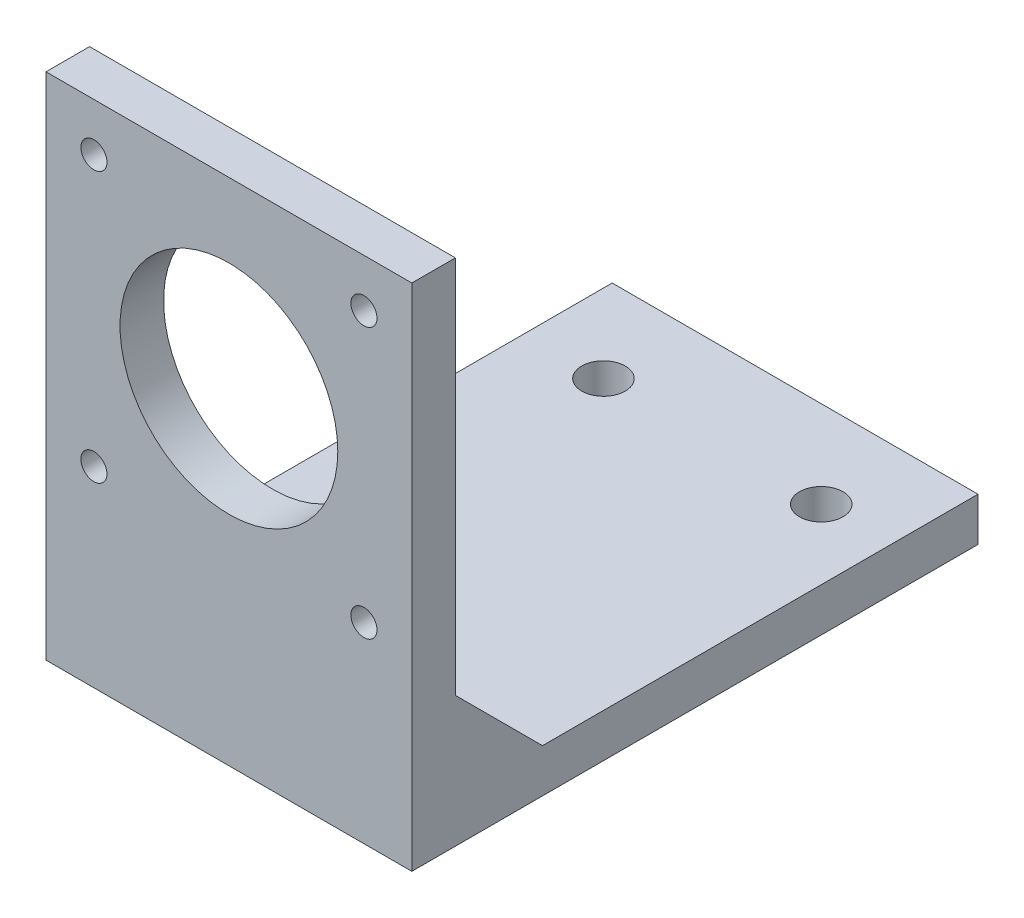
SolidWorks part; units mm, degrees
ref_plane "前视基准面" through (0, 0, 0) normal (0, 0, 1) x (1, 0, 0)
ref_plane "上视基准面" through (0, 0, 0) normal (0, 1, 0) x (1, 0, 0)
ref_plane "右视基准面" through (0, 0, 0) normal (1, 0, 0) x (0, 0, -1)
sketch "草图1" plane through (0, 0, 0) normal (0, 1, 0) x (0, 0, -1)
  line L1 (0, 0) -> (-60, 0)
  line L2 (0, 0) -> (0, 42)
  line L3 (0, 42) -> (-60, 42)
  line L4 (-60, 0) -> (-60, 42)
  circle A0 centre (-10, 33) radius 2.5
  circle A1 centre (-10, 8) radius 2.5
  dimension "D3" = 25
  dimension "D4" = 5
  dimension "D5" = 8
  dimension "D1" = 42
  dimension "D2" = 60
  dimension "D6" = 10
extrude "凸台-拉伸1" add sketch "草图1" along normal blind 5
sketch "草图2" plane through (0, 0, 60) normal (0, 0, 1) x (1, 0, 0)
  line L0 (0, 5) -> (0, 0) construction
  line L5 (-42, 0) -> (0, 0)
  line L6 (-42, 0) -> (-42, 58.5)
  line L7 (-42, 58.5) -> (0, 58.5)
  line L8 (0, 0) -> (0, 58.5)
  line L9 (-36.5, 53) -> (-5.5, 53) construction
  line L10 (-5.5, 53) -> (-5.5, 22) construction
  circle A0 centre (-21, 37.5) radius 12.5
  circle A1 centre (-36.5, 53) radius 1.5
  circle A2 centre (-36.5, 22) radius 1.5
  circle A3 centre (-5.5, 53) radius 1.5
  circle A4 centre (-5.5, 22) radius 1.5
  point P11 (-21, 0)
  point P19 (-21, 53)
  point P20 (-5.5, 37.5)
  point P25 (-21, 58.5)
  dimension "D1" = 37.5
  dimension "D2" = 25
  dimension "D4" = 3
  dimension "D3" = 58.5
  dimension "D5" = 31
  dimension "D6" = 31
extrude "凸台-拉伸2" add sketch "草图2" along normal blind 5
sketch "草图3" plane through (0, 0, 0) normal (1, 0, 0) x (0, 0, -1)
  line L0 (-60, 15) -> (-60, 5)
  line L1 (-60, 5) -> (-60, 58.5) construction
  line L2 (-60, 5) -> (-50, 5)
  line L3 (-60, 5) -> (0, 5) construction
  line L4 (-50, 5) -> (-60, 15)
  dimension "D1" = 10
extrude "凸台-拉伸3" add sketch "草图3" against normal blind 5
pattern_linear "阵列(线性)1" count 2 spacing 37 along (-1, 0, 0) of "凸台-拉伸3"
